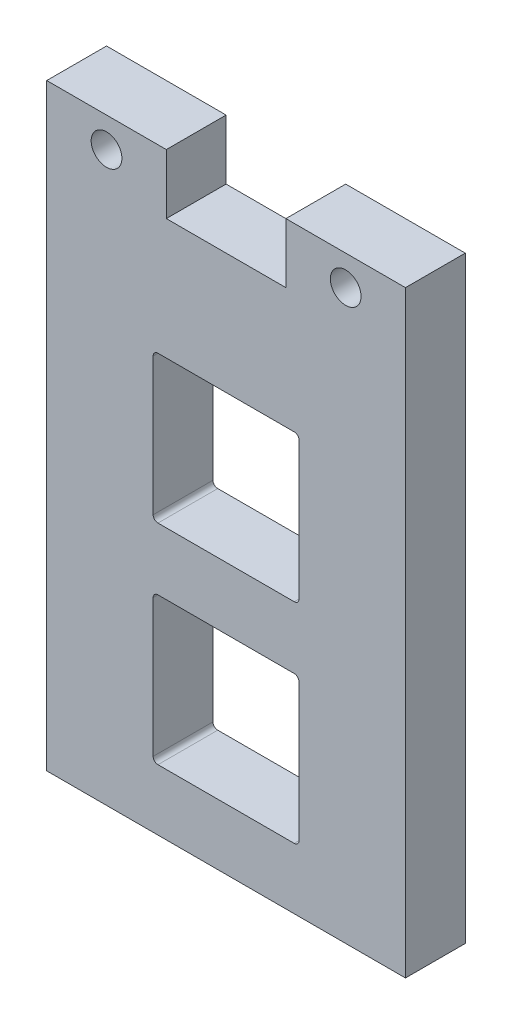
SolidWorks part; units mm, degrees
material "Beech"
ref_plane "Front Plane" through (0, 0, 0) normal (0, 0, 1) x (1, 0, 0)
ref_plane "Top Plane" through (0, 0, 0) normal (0, 1, 0) x (1, 0, 0)
ref_plane "Right Plane" through (0, 0, 0) normal (1, 0, 0) x (0, 0, -1)
sketch "Sketch1" plane through (0, 0, 0) normal (0, 0, 1) x (1, 0, 0)
  line L1 (0, 0) -> (38.1, 0)
  line L2 (0, 0) -> (0, -63.5)
  line L3 (0, -63.5) -> (38.1, -63.5)
  line L4 (38.1, -63.5) -> (38.1, 0)
  dimension "D1" = 63.5
  dimension "D2" = 38.1
extrude "Boss-Extrude1" add sketch "Sketch1" along normal mid plane 6.35
sketch "Sketch2" [suppressed] plane through (0, 0, 3.175) normal (0, 0, 1) x (1, 0, 0)
  line L0 (6.2865, 0) -> (18.9865, 0)
  line L1 (6.2865, 0) -> (6.2865, -6.35)
  line L3 (18.9865, 0) -> (18.9865, -6.35)
  line L4 (76.2, -12.7) -> (76.2, 0) construction
  line L16 (76.2, 0) -> (0, 0) construction
  line L17 (14.1605, -13.97) -> (14.1605, -17.78)
  line L18 (16.4465, -13.97) -> (14.1605, -13.97)
  line L19 (16.4465, -11.43) -> (16.4465, -13.97)
  line L20 (14.1605, -11.43) -> (16.4465, -11.43)
  line L21 (11.1125, -13.97) -> (11.1125, -17.78)
  line L22 (8.8265, -13.97) -> (11.1125, -13.97)
  line L23 (8.8265, -11.43) -> (8.8265, -13.97)
  line L24 (11.1125, -11.43) -> (8.8265, -11.43)
  line L25 (11.1125, -6.35) -> (11.1125, -11.43)
  line L26 (14.1605, -17.78) -> (11.1125, -17.78)
  line L27 (14.1605, -6.35) -> (14.1605, -11.43)
  line L28 (14.1605, -6.35) -> (18.9865, -6.35)
  line L29 (6.2865, -6.35) -> (11.1125, -6.35)
  line L35 (12.6365, 0) -> (12.6365, -17.78) construction
  dimension "D1" = 12.7
  dimension "D2" = 6.35
  dimension "D3" = 11.43
  dimension "D4" = 13.97
  dimension "D5" = 17.78
  dimension "D6" = 3.048
  dimension "D7" = 3.048
  dimension "D8" = 7.62
  dimension "D9" = 3.81
  dimension "D10" = 1.524
  dimension "D11" = 65.0875
sketch "Sketch3" plane through (0, 0, 3.175) normal (0, 0, 1) x (1, 0, 0)
  line L1 (0, 0) -> (12.7, 0)
  line L2 (0, 0) -> (0, -12.7)
  line L3 (0, -12.7) -> (12.7, -12.7)
  line L4 (12.7, 0) -> (12.7, -12.7)
  dimension "D1" = 12.7
  dimension "D2" = 12.7
extrude "Cut-Extrude2" [suppressed] cut sketch "Sketch3" against normal up to next contours L3 L4 L1 L2
hole_wizard "#4 Clearance Hole1" positions "Sketch5" profile "Sketch4" hole size "#4" standard "ANSI Inch" end condition up to next
sketch "Sketch5" plane through (0, 0, 3.175) normal (0, 0, 1) x (1, 0, 0)
  line L0 (0, -3.175) -> (38.1, -3.175) construction
  line L1 (0, 0) -> (0, -63.5) construction
  line L2 (38.1, -63.5) -> (38.1, 0) construction
  line L4 (38.1, 0) -> (0, 0) construction
  point P0 (6.35, -3.175)
  point P13 (31.75, -3.175)
  dimension "D1" = 3.175
  dimension "D2" = 6.35
  dimension "D3" = 6.35
sketch "Sketch4" plane through (6.35, -3.175, 3.175) normal (1, 0, 0) x (0, -1, 0)
  line L0 (0, 0) -> (0, 6.35)
  line L1 (0, 6.35) -> (1.6319, 6.35)
  line L2 (1.6319, 6.35) -> (1.6319, 0)
  line L5 (1.6319, 0) -> (0, 0)
  line L11 (0, -6.35) -> (0, 107.95) construction
  dimension "Thru Hole Dia." = 3.2639
  dimension "Thru Hole Depth" = 6.35
sketch "Sketch6" plane through (0, 0, 3.175) normal (0, 0, 1) x (1, 0, 0)
  line L0 (19.05, 0) -> (19.05, -63.5) construction
  line L1 (38.1, 0) -> (0, 0) construction
  line L2 (0, -63.5) -> (38.1, -63.5) construction
  line L3 (25.4, -6.35) -> (12.7, -6.35)
  line L4 (25.4, -6.35) -> (25.4, 0)
  line L5 (12.7, -6.35) -> (12.7, 0)
  line L6 (25.4, 0) -> (12.7, 0)
  line L7 (25.4, -6.35) -> (12.7, 0) construction
  line L8 (12.7, -6.35) -> (25.4, 0) construction
  point P7 (19.05, -3.175)
  dimension "D1" = 12.7
  dimension "D2" = 6.35
extrude "Cut-Extrude3" cut sketch "Sketch6" against normal up to next
hole_wizard "#4 Clearance Hole2" positions "Sketch9" profile "Sketch8" hole size "#4" standard "ANSI Inch"
sketch "Sketch9" plane through (0, 0, 3.175) normal (0, 0, 1) x (1, 0, 0)
  point P0 (10.5046, -14.725)
  point P3 (36.4854, -14.725)
  point P6 (23.495, -37.225)
sketch "Sketch8" plane through (10.5046, -14.725, 3.175) normal (1, 0, 0) x (0, -1, 0)
  line L0 (0, 0) -> (0, 6.35)
  line L1 (0, 6.35) -> (1.6319, 6.35)
  line L2 (1.6319, 6.35) -> (1.6319, 0)
  line L5 (1.6319, 0) -> (0, 0)
  line L11 (0, -6.35) -> (0, 107.95) construction
  dimension "Thru Hole Dia." = 3.2639
  dimension "Thru Hole Depth" = 6.35
ref_plane "Plane1" through (0, -3.175, 0) normal (0, 1, 0) x (1, 0, 0)
ref_plane "Plane2" through (19.05, 0, 0) normal (-1, 0, 0) x (0, 0, 1)
sketch "Sketch10" plane through (0, 0, -3.175) normal (0, 0, -1) x (-1, 0, 0)
  line L0 (-19.05, -19.05) -> (-19.05, -38.4393) construction
  line L1 (-11.938, -19.05) -> (-26.162, -19.05) construction
  line L2 (-10.033, -26.9875) -> (-31.4077, -26.9875) construction
  line L3 (-10.033, -32.385) -> (-10.033, -21.59) construction
  line L5 (-26.797, -34.798) -> (-11.303, -34.798)
  line L6 (-26.797, -34.798) -> (-26.797, -19.177)
  line L7 (-26.797, -19.177) -> (-11.303, -19.177)
  line L8 (-11.303, -34.798) -> (-11.303, -19.177)
  line L9 (-26.797, -34.798) -> (-11.303, -19.177) construction
  line L10 (-26.797, -19.177) -> (-11.303, -34.798) construction
  point P8 (-19.05, -26.9875)
  dimension "D1" = 15.621
  dimension "D2" = 15.494
extrude "Cut-Extrude4" cut sketch "Sketch10" against normal up to next
pattern_linear "LPattern1" count 2 spacing 22.225 along (0, -1, 0) of "Cut-Extrude4"
fillet "Fillet1" radius 0.508 8 edges at (26.797, -41.402, 0) (11.303, -41.402, 0) (11.303, -57.023, 0) (26.797, -57.023, 0) (26.797, -34.798, 0) (11.303, -34.798, 0) (11.303, -19.177, 0) (26.797, -19.177, 0)
